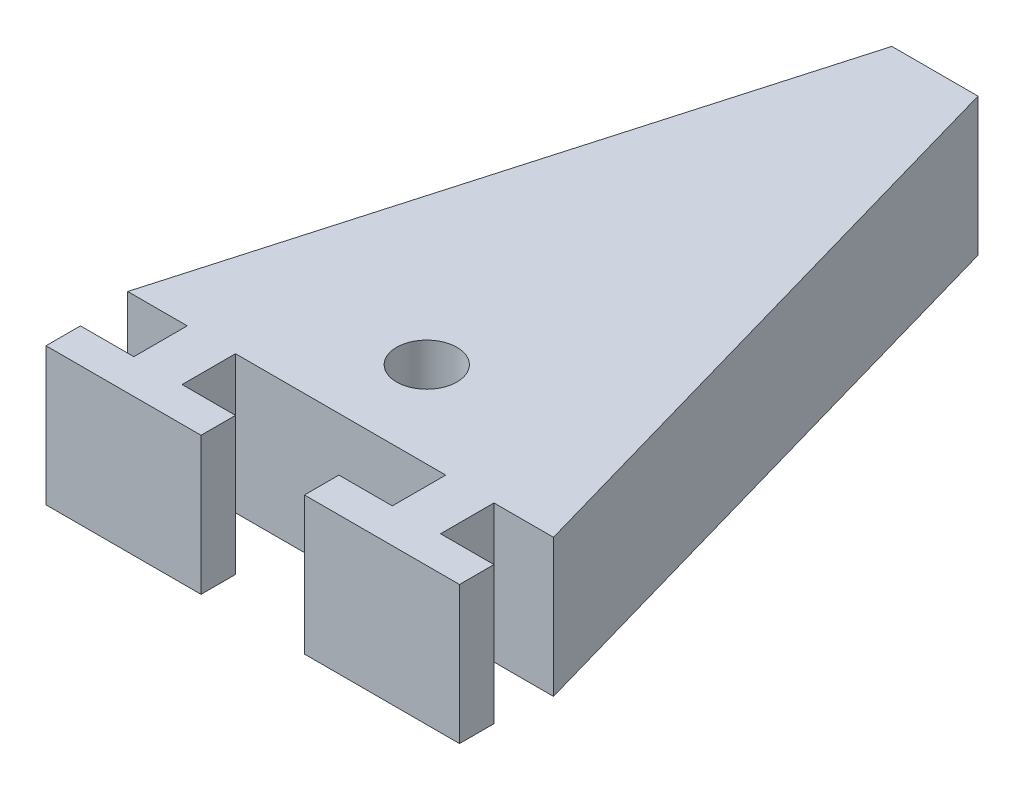
SolidWorks part; units mm, degrees
ref_plane "Plan de face" through (0, 0, 0) normal (0, 0, 1) x (1, 0, 0)
ref_plane "Plan de dessus" through (0, 0, 0) normal (0, 1, 0) x (1, 0, 0)
ref_plane "Plan de droite" through (0, 0, 0) normal (1, 0, 0) x (0, 0, -1)
sketch "Sketch2" plane through (0, 0, 0) normal (0, 1, 0) x (1, 0, 0)
  line L1 (12.5, 0) -> (2.5, 35)
  line L2 (2.5, 35) -> (-2.5, 35)
  line L3 (-2.5, 35) -> (-12.5, 0)
  line L13 (-12.5, 0) -> (12.5, 0)
  point P5 (0, 0)
  dimension "D1" = 25
  dimension "D2" = 5
  dimension "D4" = 35
extrude "Boss-Extrude1" add sketch "Sketch2" along normal blind 8
sketch "Esquisse2" plane through (0, 0, 0) normal (0, 1, 0) x (1, 0, 0)
  line L0 (-8.9017, 0) -> (-8.9017, -2.6)
  line L1 (-12.5, 0) -> (12.5, 0) construction
  line L2 (-8.9017, -2.6) -> (-12.0017, -2.6)
  line L3 (-12.0017, -2.6) -> (-12.0017, -4.6)
  line L4 (-12.0017, -4.6) -> (-3.0017, -4.6)
  line L5 (-3.0017, -4.6) -> (-3.0017, -2.6)
  line L6 (-3.0017, -2.6) -> (-6.1017, -2.6)
  line L7 (-6.1017, -2.6) -> (-6.1017, 0)
  line L8 (-6.1017, 0) -> (-8.9017, 0)
  point P10 (-7.5017, 0)
  dimension "D1" = 9
  dimension "D2" = 7.5017
  dimension "D3" = 2
  dimension "D4" = 2.6
  dimension "D5" = 2.8
extrude "Boss.-Extru.1" add sketch "Esquisse2" along normal blind 8
mirror "Symétrie1" about plane through (0, 0, 0) normal (1, 0, 0) of "Boss.-Extru.1"
sketch "Esquisse3" plane through (0, 8, 0) normal (0, 1, 0) x (1, 0, 0)
  line L0 (-12.5, 0) -> (-8.9017, 0)
  line L1 (-8.9017, 0) -> (-8.9017, 0.5)
  line L2 (-8.9017, 0.5) -> (-12.3571, 0.5)
  line L3 (-2.5, 35) -> (-12.5, 0) construction
  line L4 (-12.3571, 0.5) -> (-12.5, 0)
  line L5 (-6.1017, 0) -> (-6.1017, 0.5)
  line L6 (-6.1017, 0.5) -> (6.1017, 0.5)
  line L7 (6.1017, 0.5) -> (6.1017, 0)
  line L8 (6.1017, 0) -> (-6.1017, 0)
  line L9 (8.9017, 0) -> (8.9017, 0.5)
  line L10 (8.9017, 0.5) -> (12.3571, 0.5)
  line L11 (12.5, 0) -> (2.5, 35) construction
  line L12 (12.3571, 0.5) -> (12.5, 0)
  line L13 (12.5, 0) -> (8.9017, 0)
  dimension "D1" = 0.5
extrude "Enlèv. mat.-Extru.1" cut sketch "Esquisse3" against normal through all
sketch "Sketch3" plane through (0, 0, 0) normal (0, -1, 0) x (1, 0, 0)
  line L0 (6.1017, -0.5) -> (-6.1017, -0.5) construction
  circle A0 centre (0, -5.5) radius 1.75
  dimension "D1" = 3.5
  dimension "D2" = 5
extrude "Cut-Extrude1" cut sketch "Sketch3" against normal through all
